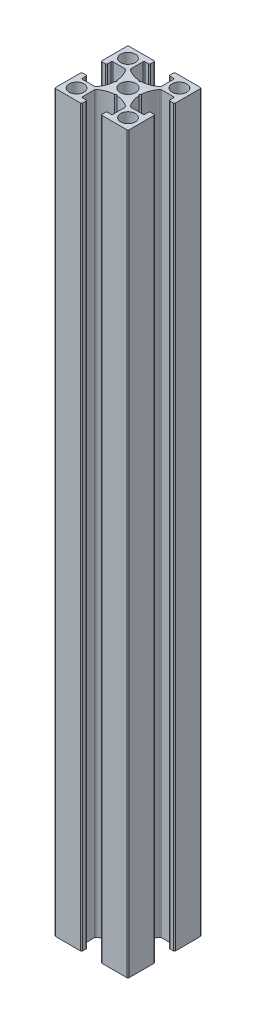
SolidWorks part; units mm, degrees
ref_plane "정면도" through (0, 0, 0) normal (0, 0, 1) x (1, 0, 0)
ref_plane "평면도" through (0, 0, 0) normal (0, 1, 0) x (1, 0, 0)
ref_plane "우측면도" through (0, 0, 0) normal (1, 0, 0) x (0, 0, -1)
sketch "스케치1" plane through (0, 0, 0) normal (0, 1, 0) x (1, 0, 0)
  line B0 (4.15, 4.9427) -> (4.15, 8.2)
  line B1 (3.85, 8.5) -> (2.95, 8.5)
  line B2 (2.65, 8.8) -> (2.65, 9.7)
  line B3 (2.95, 10) -> (9.7, 10)
  line B4 (10, 9.7) -> (10, 2.95)
  line B5 (9.7, 2.65) -> (8.8, 2.65)
  line B6 (8.5, 2.95) -> (8.5, 3.85)
  line B7 (8.2, 4.15) -> (4.9427, 4.15)
  line B8 (3.3073, 0.3073) -> (3, 0)
  line B9 (3, 0) -> (3.3073, -0.3073)
  line B10 (4.9427, -4.15) -> (8.2, -4.15)
  line B11 (8.5, -3.85) -> (8.5, -2.95)
  line B12 (8.8, -2.65) -> (9.7, -2.65)
  line B13 (10, -2.95) -> (10, -9.7)
  line B14 (9.7, -10) -> (2.95, -10)
  line B15 (2.65, -9.7) -> (2.65, -8.8)
  line B16 (2.95, -8.5) -> (3.85, -8.5)
  line B17 (4.15, -8.2) -> (4.15, -4.9427)
  line B18 (0.3073, -3.3073) -> (0, -3)
  line B19 (0, -3) -> (-0.3073, -3.3073)
  line B20 (-4.15, -4.9427) -> (-4.15, -8.2)
  line B21 (-3.85, -8.5) -> (-2.95, -8.5)
  line B22 (-2.65, -8.8) -> (-2.65, -9.7)
  line B23 (-2.95, -10) -> (-9.7, -10)
  line B24 (-10, -9.7) -> (-10, -2.95)
  line B25 (-9.7, -2.65) -> (-8.8, -2.65)
  line B26 (-8.5, -2.95) -> (-8.5, -3.85)
  line B27 (-8.2, -4.15) -> (-4.9427, -4.15)
  line B28 (-3.3073, -0.3073) -> (-3, 0)
  line B29 (-3, 0) -> (-3.3073, 0.3073)
  line B30 (-4.9427, 4.15) -> (-8.2, 4.15)
  line B31 (-8.5, 3.85) -> (-8.5, 2.95)
  line B32 (-8.8, 2.65) -> (-9.7, 2.65)
  line B33 (-10, 2.95) -> (-10, 9.7)
  line B34 (-9.7, 10) -> (-2.95, 10)
  line B35 (-2.65, 9.7) -> (-2.65, 8.8)
  line B36 (-2.95, 8.5) -> (-3.85, 8.5)
  line B37 (-4.15, 8.2) -> (-4.15, 4.9427)
  line B38 (-0.3073, 3.3073) -> (0, 3)
  line B39 (0, 3) -> (0.3073, 3.3073)
  line B40 (-9.5, 7) -> (-4.5, 7) construction
  line B41 (-7, 9.5) -> (-7, 4.5) construction
  line B42 (-9.5, -7) -> (-4.5, -7) construction
  line B43 (-7, -9.5) -> (-7, -4.5) construction
  line B44 (9.5, 7) -> (4.5, 7) construction
  line B45 (7, 9.5) -> (7, 4.5) construction
  line B46 (7, -9.5) -> (7, -4.5) construction
  line B47 (9.5, -7) -> (4.5, -7) construction
  circle B48 centre (0, 0) radius 2.15
  arc B49 (4.15, 8.2) -> (3.85, 8.5) centre (3.85, 8.2) ccw
  arc B50 (2.65, 8.8) -> (2.95, 8.5) centre (2.95, 8.8) ccw
  arc B51 (2.95, 10) -> (2.65, 9.7) centre (2.95, 9.7) ccw
  arc B52 (10, 9.7) -> (9.7, 10) centre (9.7, 9.7) ccw
  arc B53 (9.7, 2.65) -> (10, 2.95) centre (9.7, 2.95) ccw
  arc B54 (8.5, 2.95) -> (8.8, 2.65) centre (8.8, 2.95) ccw
  arc B55 (8.5, 3.85) -> (8.2, 4.15) centre (8.2, 3.85) ccw
  arc B56 (4.9427, 4.15) -> (4.7078, 4.0366) centre (4.9427, 3.85) ccw
  arc B57 (4.7078, 4.0366) -> (3.3073, 0.3073) centre (9.7908, 0) ccw
  arc B58 (3.3073, -0.3073) -> (4.7078, -4.0366) centre (9.7908, 0) ccw
  arc B59 (4.7078, -4.0366) -> (4.9427, -4.15) centre (4.9427, -3.85) ccw
  arc B60 (8.2, -4.15) -> (8.5, -3.85) centre (8.2, -3.85) ccw
  arc B61 (8.8, -2.65) -> (8.5, -2.95) centre (8.8, -2.95) ccw
  arc B62 (10, -2.95) -> (9.7, -2.65) centre (9.7, -2.95) ccw
  arc B63 (9.7, -10) -> (10, -9.7) centre (9.7, -9.7) ccw
  arc B64 (2.65, -9.7) -> (2.95, -10) centre (2.95, -9.7) ccw
  arc B65 (2.95, -8.5) -> (2.65, -8.8) centre (2.95, -8.8) ccw
  arc B66 (3.85, -8.5) -> (4.15, -8.2) centre (3.85, -8.2) ccw
  arc B67 (4.15, -4.9427) -> (4.0366, -4.7078) centre (3.85, -4.9427) ccw
  arc B68 (4.0366, -4.7078) -> (0.3073, -3.3073) centre (0, -9.7908) ccw
  arc B69 (-0.3073, -3.3073) -> (-4.0366, -4.7078) centre (0, -9.7908) ccw
  arc B70 (-4.0366, -4.7078) -> (-4.15, -4.9427) centre (-3.85, -4.9427) ccw
  arc B71 (-4.15, -8.2) -> (-3.85, -8.5) centre (-3.85, -8.2) ccw
  arc B72 (-2.65, -8.8) -> (-2.95, -8.5) centre (-2.95, -8.8) ccw
  arc B73 (-2.95, -10) -> (-2.65, -9.7) centre (-2.95, -9.7) ccw
  arc B74 (-10, -9.7) -> (-9.7, -10) centre (-9.7, -9.7) ccw
  arc B75 (-9.7, -2.65) -> (-10, -2.95) centre (-9.7, -2.95) ccw
  arc B76 (-8.5, -2.95) -> (-8.8, -2.65) centre (-8.8, -2.95) ccw
  arc B77 (-8.5, -3.85) -> (-8.2, -4.15) centre (-8.2, -3.85) ccw
  arc B78 (-4.9427, -4.15) -> (-4.7078, -4.0366) centre (-4.9427, -3.85) ccw
  arc B79 (-4.7078, -4.0366) -> (-3.3073, -0.3073) centre (-9.7908, 0) ccw
  arc B80 (-3.3073, 0.3073) -> (-4.7078, 4.0366) centre (-9.7908, 0) ccw
  arc B81 (-4.7078, 4.0366) -> (-4.9427, 4.15) centre (-4.9427, 3.85) ccw
  arc B82 (-8.2, 4.15) -> (-8.5, 3.85) centre (-8.2, 3.85) ccw
  arc B83 (-8.8, 2.65) -> (-8.5, 2.95) centre (-8.8, 2.95) ccw
  arc B84 (-10, 2.95) -> (-9.7, 2.65) centre (-9.7, 2.95) ccw
  arc B85 (-9.7, 10) -> (-10, 9.7) centre (-9.7, 9.7) ccw
  arc B86 (-2.65, 9.7) -> (-2.95, 10) centre (-2.95, 9.7) ccw
  arc B87 (-2.95, 8.5) -> (-2.65, 8.8) centre (-2.95, 8.8) ccw
  arc B88 (-3.85, 8.5) -> (-4.15, 8.2) centre (-3.85, 8.2) ccw
  arc B89 (-4.15, 4.9427) -> (-4.0366, 4.7078) centre (-3.85, 4.9427) ccw
  arc B90 (-4.0366, 4.7078) -> (-0.3073, 3.3073) centre (0, 9.7908) ccw
  arc B91 (0.3073, 3.3073) -> (4.0366, 4.7078) centre (0, 9.7908) ccw
  arc B92 (4.0366, 4.7078) -> (4.15, 4.9427) centre (3.85, 4.9427) ccw
  circle B93 centre (-7, 7) radius 2
  circle B94 centre (-7, -7) radius 2
  circle B95 centre (7, 7) radius 2
  circle B96 centre (7, -7) radius 2
sketch_block_instance "블록1-1"
sketch_block "블록1"
extrude "보스-돌출1" add sketch "스케치1" along normal blind 200 contours B92 B91 B39 B38 B90 B89 B37 B88 B36 B87 B35 B86 B34 B85 B33 B84 B32 B83 B31 B82 B30 B81 B80 B29 B28 B79 B78 B27 B77 B26 B76 B25 B75 B24 B74 B23 B73 B22 B72 B21 B71 B20 B70 B69 B19 B18 B68 B67 B17 B66 B16
